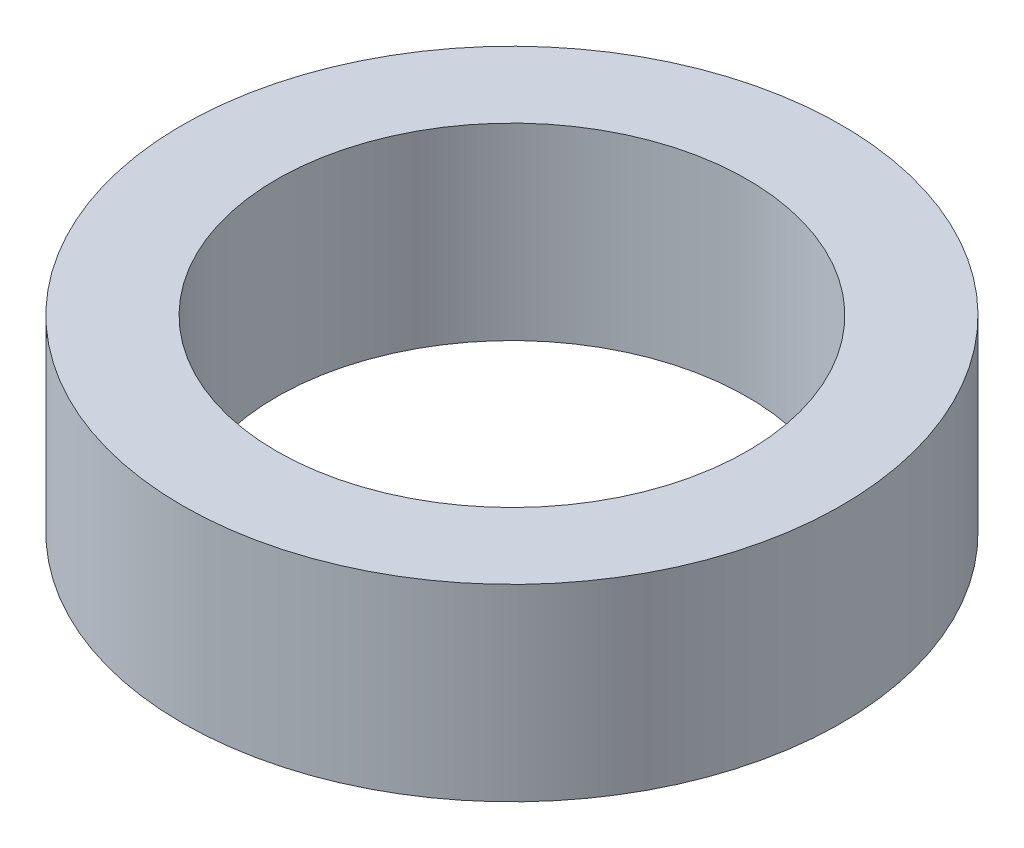
SolidWorks part; units mm, degrees
ref_plane "정면" through (0, 0, 0) normal (0, 0, 1) x (1, 0, 0)
ref_plane "윗면" through (0, 0, 0) normal (0, 1, 0) x (1, 0, 0)
ref_plane "우측면" through (0, 0, 0) normal (1, 0, 0) x (0, 0, -1)
sketch "스케치1" plane through (0, 0, 0) normal (0, 1, 0) x (1, 0, 0)
  circle A0 centre (0, 0) radius 14
  circle A1 centre (0, 0) radius 10
  dimension "D1" = 20
  dimension "D2" = 28
extrude "보스-돌출1" add sketch "스케치1" along normal blind 8
